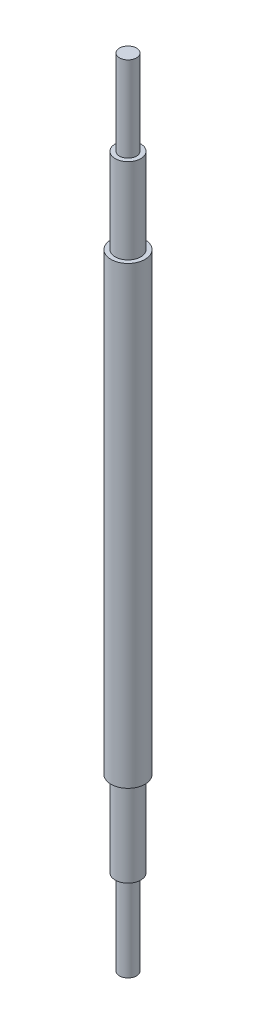
SolidWorks part; units mm, degrees
ref_plane "前视基准面" through (0, 0, 0) normal (0, 0, 1) x (1, 0, 0)
ref_plane "上视基准面" through (0, 0, 0) normal (0, 1, 0) x (1, 0, 0)
ref_plane "右视基准面" through (0, 0, 0) normal (1, 0, 0) x (0, 0, -1)
sketch "草图1" plane through (0, 0, 0) normal (0, 1, 0) x (1, 0, 0)
  circle A0 centre (0, 0) radius 4
  dimension "D1" = 8
extrude "凸台-拉伸1" add sketch "草图1" along normal blind 106.8
sketch "草图2" plane through (0, 106.8, 0) normal (0, 1, 0) x (1, 0, 0)
  circle A0 centre (0, 0) radius 3
  dimension "D1" = 6
extrude "凸台-拉伸2" add sketch "草图2" along normal blind 20
sketch "草图3" plane through (0, 126.8, 0) normal (0, 1, 0) x (1, 0, 0)
  circle A0 centre (0, 0) radius 2
  dimension "D1" = 4
extrude "凸台-拉伸3" add sketch "草图3" along normal blind 20
sketch "草图4" plane through (0, 0, 0) normal (0, -1, 0) x (1, 0, 0)
  circle A0 centre (0, 0) radius 3
  dimension "D1" = 6
extrude "凸台-拉伸4" add sketch "草图4" along normal blind 20
sketch "草图5" plane through (0, -20, 0) normal (0, -1, 0) x (1, 0, 0)
  circle A0 centre (0, 0) radius 2
  dimension "D1" = 4
extrude "凸台-拉伸5" add sketch "草图5" along normal blind 20
